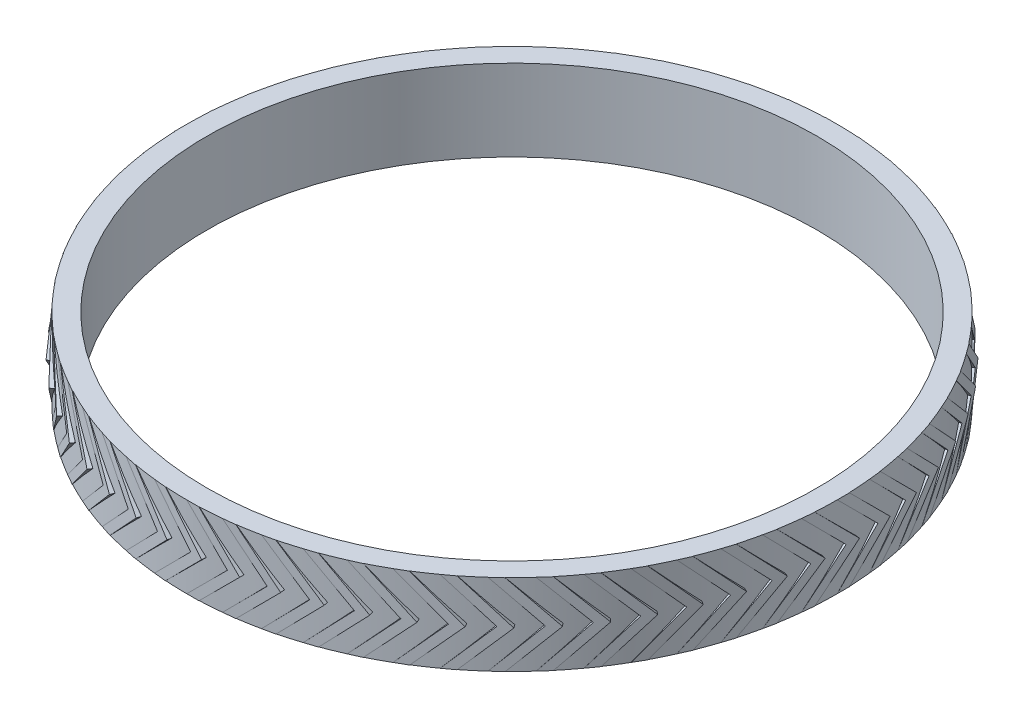
SolidWorks part; units mm, degrees
ref_plane "Front Plane" through (0, 0, 0) normal (0, 0, 1) x (1, 0, 0)
ref_plane "Top Plane" through (0, 0, 0) normal (0, 1, 0) x (1, 0, 0)
ref_plane "Right Plane" through (0, 0, 0) normal (1, 0, 0) x (0, 0, -1)
sketch "Sketch1" plane through (0, 0, 0) normal (1, 0, 0) x (0, 0, -1)
  line L0 (0, 0) -> (-95.25, 0) construction
  line L1 (-95.25, -12.7) -> (-101.6, -12.7)
  line L3 (-95.25, -12.7) -> (-95.25, 12.7)
  line L4 (-95.25, 12.7) -> (-101.6, 12.7)
  line L5 (-101.6, -12.7) -> (-101.6, 12.7)
  line L6 (0, 0) -> (0, 34.4916) construction
  dimension "D1" = 95.25
  dimension "D2" = 6.35
  dimension "D3" = 12.7
revolve "Revolve1" add sketch "Sketch1" angle 360 about L6
ref_plane "Plane1" through (-101.6, 0, 0) normal (-1, 0, 0) x (0, 0, 1)
sketch "Sketch2" plane through (-101.6, 0, 0) normal (-1, 0, 0) x (0, 0, 1)
  line L0 (0, 12.7) -> (12.7, 0)
  line L1 (101.6, 12.7) -> (-101.6, 12.7) construction
  line L2 (12.7, 0) -> (0, -12.7)
  line L3 (-101.6, -12.7) -> (101.6, -12.7) construction
  line L4 (0, 12.7) -> (3.81, 12.7)
  line L5 (95.25, 12.7) -> (-95.25, 12.7) construction
  line L6 (3.81, 12.7) -> (16.51, 0)
  line L9 (-1000, 0) -> (49000, 0) construction
  line L10 (0, -12.7) -> (3.81, -12.7)
  line L11 (3.81, -12.7) -> (16.51, 0)
  dimension "D1" = 3.81
extrude "Boss-Extrude1" add sketch "Sketch2" against normal blind 2.54
pattern_circular "CirPattern1" count 60 over 360 about axis through (0, 0, 0) along (0, 1, 0) of "Boss-Extrude1"
